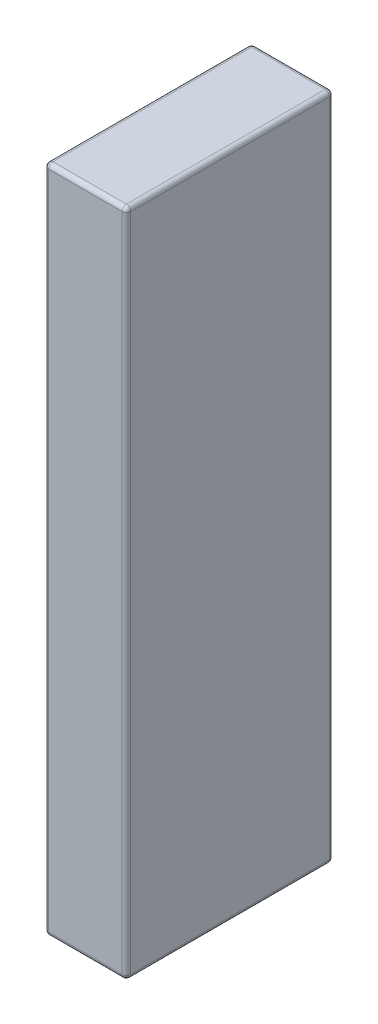
SolidWorks part; units mm, degrees
material "HRB 5000mah 11.1v Battery"
ref_plane "Front Plane" through (0, 0, 0) normal (0, 0, 1) x (1, 0, 0)
ref_plane "Top Plane" through (0, 0, 0) normal (0, 1, 0) x (1, 0, 0)
ref_plane "Right Plane" through (0, 0, 0) normal (1, 0, 0) x (0, 0, -1)
sketch "Sketch1" plane through (0, 0, 0) normal (0, 0, 1) x (1, 0, 0)
  line L1 (9.5, 77.5) -> (-9.5, 77.5)
  line L2 (9.5, 77.5) -> (9.5, -77.5)
  line L3 (9.5, -77.5) -> (-9.5, -77.5)
  line L4 (-9.5, 77.5) -> (-9.5, -77.5)
  line L5 (9.5, 77.5) -> (-9.5, -77.5) construction
  line L6 (9.5, -77.5) -> (-9.5, 77.5) construction
  point P0 (0, 0)
  dimension "D1" = 155
  dimension "D2" = 19
extrude "Boss-Extrude1" add sketch "Sketch1" along normal blind 48
fillet "Fillet1" radius 1 12 edges at (-9.5, 77.5, 24) (-9.5, -77.5, 24) (9.5, -77.5, 24) (9.5, 77.5, 24) (0, -77.5, 0) (9.5, 0, 0) (0, 77.5, 0) (-9.5, 0, 0) (0, 77.5, 48) (9.5, 0, 48) (0, -77.5, 48) (-9.5, 0, 48)
